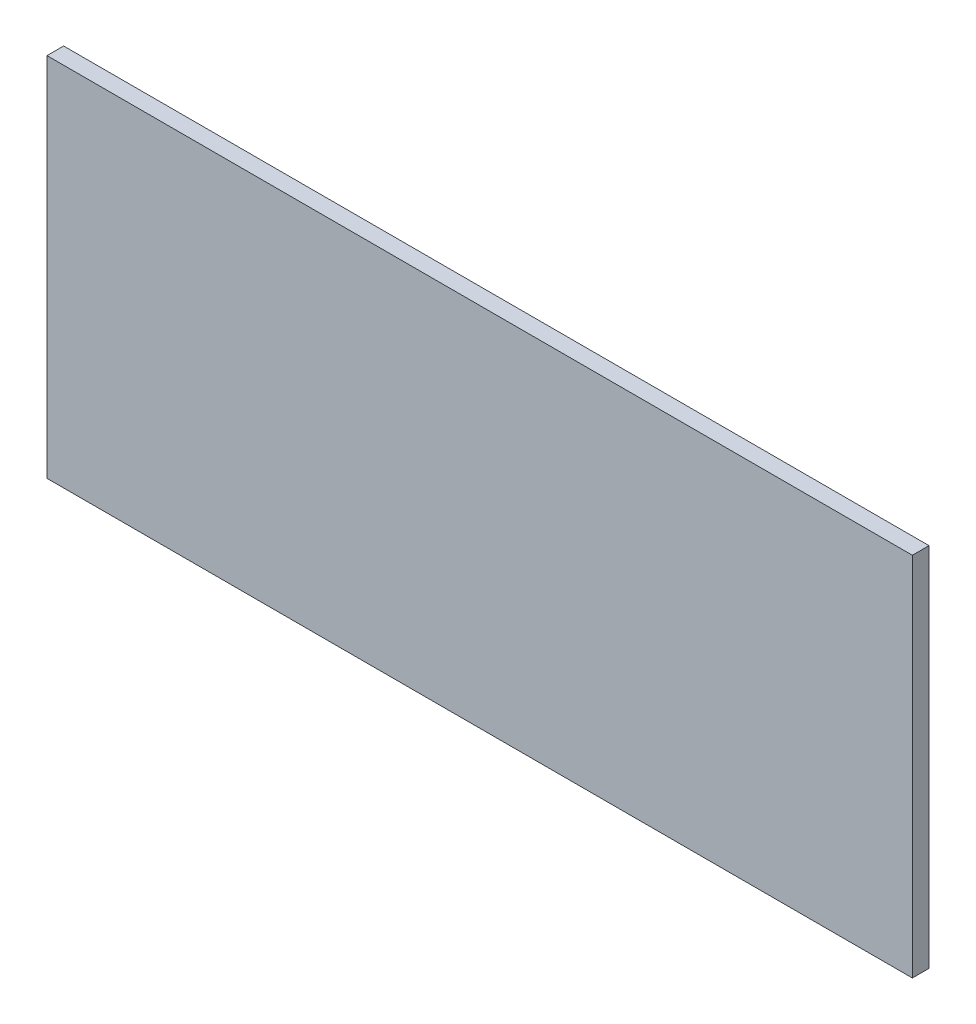
SolidWorks part; units mm, degrees
ref_plane "Front Plane" through (0, 0, 0) normal (0, 0, 1) x (1, 0, 0)
ref_plane "Top Plane" through (0, 0, 0) normal (0, 1, 0) x (1, 0, 0)
ref_plane "Right Plane" through (0, 0, 0) normal (1, 0, 0) x (0, 0, -1)
sketch "Sketch1" plane through (0, 0, 0) normal (0, 0, 1) x (1, 0, 0)
  line L1 (-78, -33) -> (78, -33)
  line L2 (-78, -33) -> (-78, 33)
  line L3 (-78, 33) -> (78, 33)
  line L4 (78, -33) -> (78, 33)
  line L5 (-78, -33) -> (78, 33) construction
  line L6 (-78, 33) -> (78, -33) construction
  point P0 (0, 0)
  dimension "D1" = 66
  dimension "D2" = 156
extrude "Boss-Extrude1" add sketch "Sketch1" along normal blind 3
